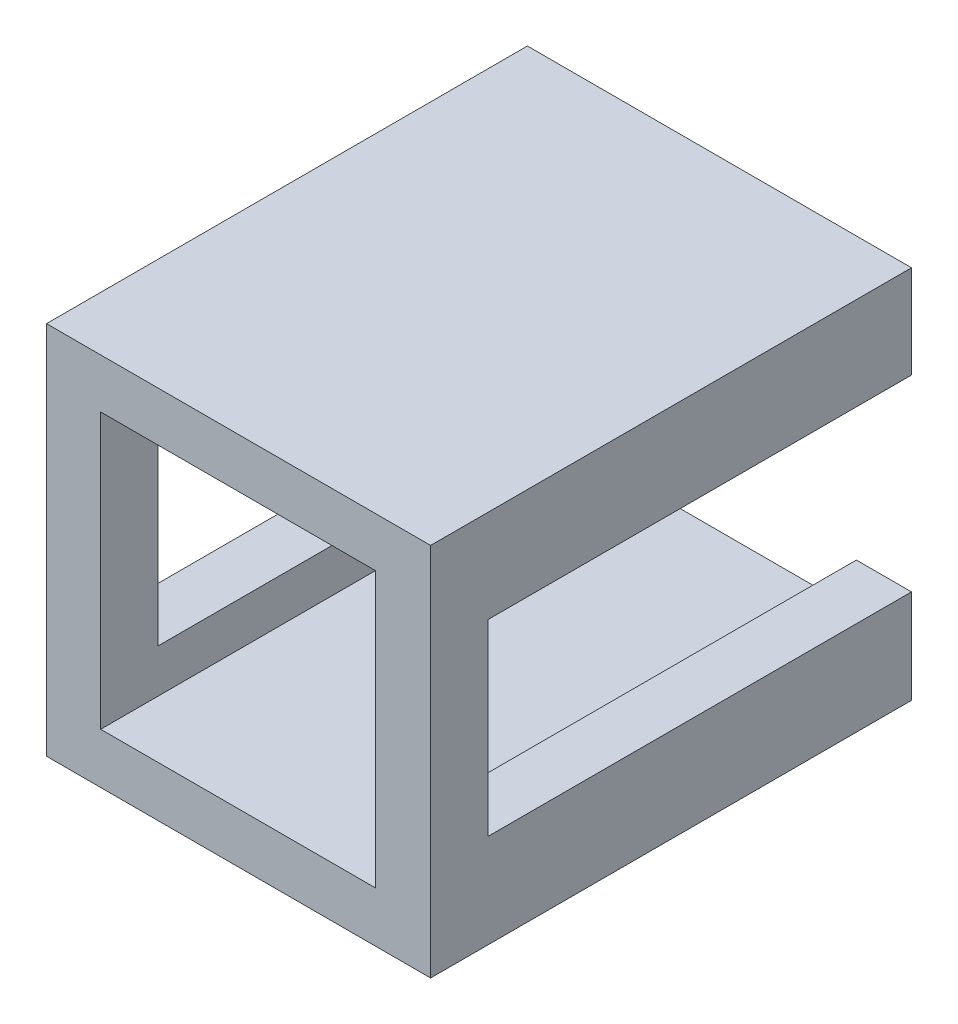
SolidWorks part; units mm, degrees
ref_plane "Front Plane" through (0, 0, 0) normal (1, 0, 0) x (0, 1, 0)
ref_plane "Top Plane" through (0, 0, 0) normal (0, 0, 1) x (0, 1, 0)
ref_plane "Right Plane" through (0, 0, 0) normal (0, 1, 0) x (-1, 0, 0)
sketch "Sketch1" plane through (0, 0, 0) normal (0, 0, 1) x (0, 1, 0)
  line L1 (-600, 600) -> (600, 600)
  line L2 (-600, 600) -> (-600, -600)
  line L3 (-600, -600) -> (600, -600)
  line L4 (600, 600) -> (600, -600)
  line L5 (-820.264, 836.6425) -> (815.7654, 836.6425)
  line L6 (-820.264, 836.6425) -> (-820.264, -840.7524)
  line L7 (-820.264, -840.7524) -> (815.7654, -840.7524)
  line L8 (815.7654, 836.6425) -> (815.7654, -840.7524)
  dimension "D1" = 1200
  dimension "D2" = 1200
  dimension "D3" = 600
  dimension "D4" = 600
  dimension "D5" = 323.2892
  dimension "D6" = 323.29
extrude "Boss-Extrude1" add sketch "Sketch1" along normal blind 2100 contours L6 L5 L8 L7
sketch "Sketch3" plane through (840.7524, 0, 0) normal (1, 0, 0) x (0, 0, -1)
  line L0 (0, -820.264) -> (0, 815.7654) construction
  line L1 (0, -410) -> (-1850, -410)
  line L2 (0, -410) -> (0, 410)
  line L3 (0, 410) -> (-1850, 410)
  line L4 (-1850, -410) -> (-1850, 410)
  point P9 (-1830.8829, 1796.1041)
  point P10 (-89.5836, 297.7759)
  dimension "D1" = 1850
  dimension "D2" = 410
  dimension "D3" = 410
extrude "Cut-Extrude1" cut sketch "Sketch3" against normal blind 2000
